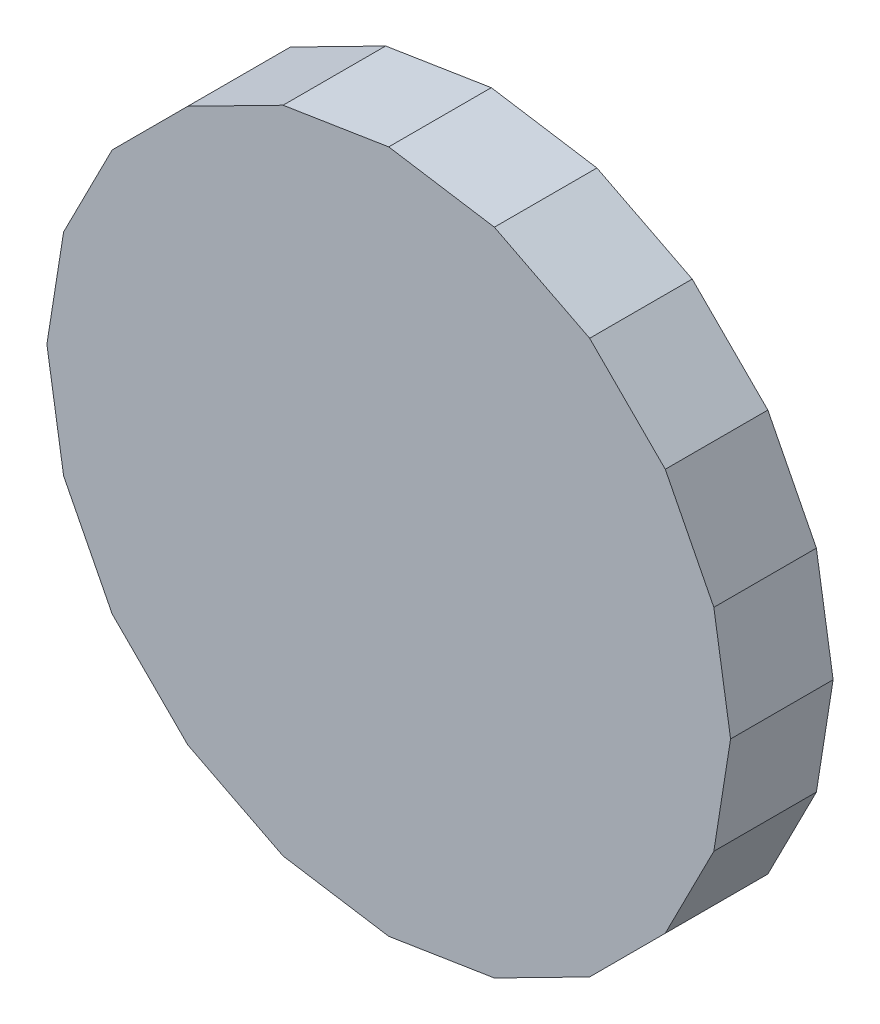
SolidWorks part; units mm, degrees
ref_plane "前视基准面" through (0, 0, 0) normal (0, 0, 1) x (1, 0, 0)
ref_plane "上视基准面" through (0, 0, 0) normal (0, 1, 0) x (1, 0, 0)
ref_plane "右视基准面" through (0, 0, 0) normal (1, 0, 0) x (0, 0, -1)
other "Configuration Table"
sketch "草图1" plane through (0, 0, 0) normal (0, 0, 1) x (1, 0, 0)
  line L1 (100, 0) -> (95.1057, 30.9017)
  line L2 (95.1057, 30.9017) -> (80.9017, 58.7785)
  line L3 (80.9017, 58.7785) -> (58.7785, 80.9017)
  line L4 (58.7785, 80.9017) -> (30.9017, 95.1057)
  line L5 (30.9017, 95.1057) -> (0, 100)
  line L6 (0, 100) -> (-30.9017, 95.1057)
  line L7 (-30.9017, 95.1057) -> (-58.7785, 80.9017)
  line L8 (-58.7785, 80.9017) -> (-80.9017, 58.7785)
  line L9 (-80.9017, 58.7785) -> (-95.1057, 30.9017)
  line L10 (-95.1057, 30.9017) -> (-100, 0)
  line L11 (-100, 0) -> (-95.1057, -30.9017)
  line L12 (-95.1057, -30.9017) -> (-80.9017, -58.7785)
  line L13 (-80.9017, -58.7785) -> (-58.7785, -80.9017)
  line L14 (-58.7785, -80.9017) -> (-30.9017, -95.1057)
  line L15 (-30.9017, -95.1057) -> (0, -100)
  line L16 (0, -100) -> (30.9017, -95.1057)
  line L17 (30.9017, -95.1057) -> (58.7785, -80.9017)
  line L18 (58.7785, -80.9017) -> (80.9017, -58.7785)
  line L19 (80.9017, -58.7785) -> (95.1057, -30.9017)
  line L20 (95.1057, -30.9017) -> (100, 0)
  circle A0 centre (0, 0) radius 98.7688 construction
extrude "凸台-拉伸1" add sketch "草图1" along normal blind 30
